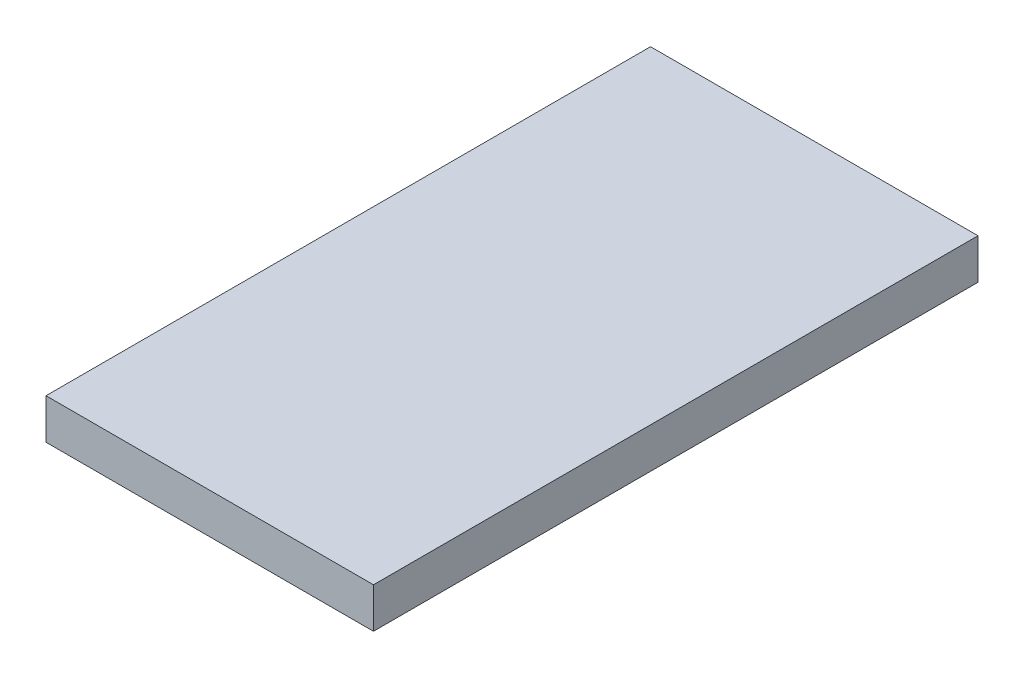
SolidWorks part; units mm, degrees
ref_plane "Front Plane" through (0, 0, 0) normal (0, 0, 1) x (1, 0, 0)
ref_plane "Top Plane" through (0, 0, 0) normal (0, 1, 0) x (1, 0, 0)
ref_plane "Right Plane" through (0, 0, 0) normal (1, 0, 0) x (0, 0, -1)
sketch "Sketch1" plane through (0, 0, 0) normal (0, 1, 0) x (1, 0, 0)
  line L1 (-41.275, 76.2) -> (41.275, 76.2)
  line L2 (-41.275, 76.2) -> (-41.275, -76.2)
  line L3 (-41.275, -76.2) -> (41.275, -76.2)
  line L4 (41.275, 76.2) -> (41.275, -76.2)
  line L5 (-41.275, 76.2) -> (41.275, -76.2) construction
  line L6 (-41.275, -76.2) -> (41.275, 76.2) construction
  point P0 (0, 0)
  dimension "D1" = 82.55
  dimension "D2" = 152.4
extrude "Boss-Extrude1" add sketch "Sketch1" along normal blind 10.16
